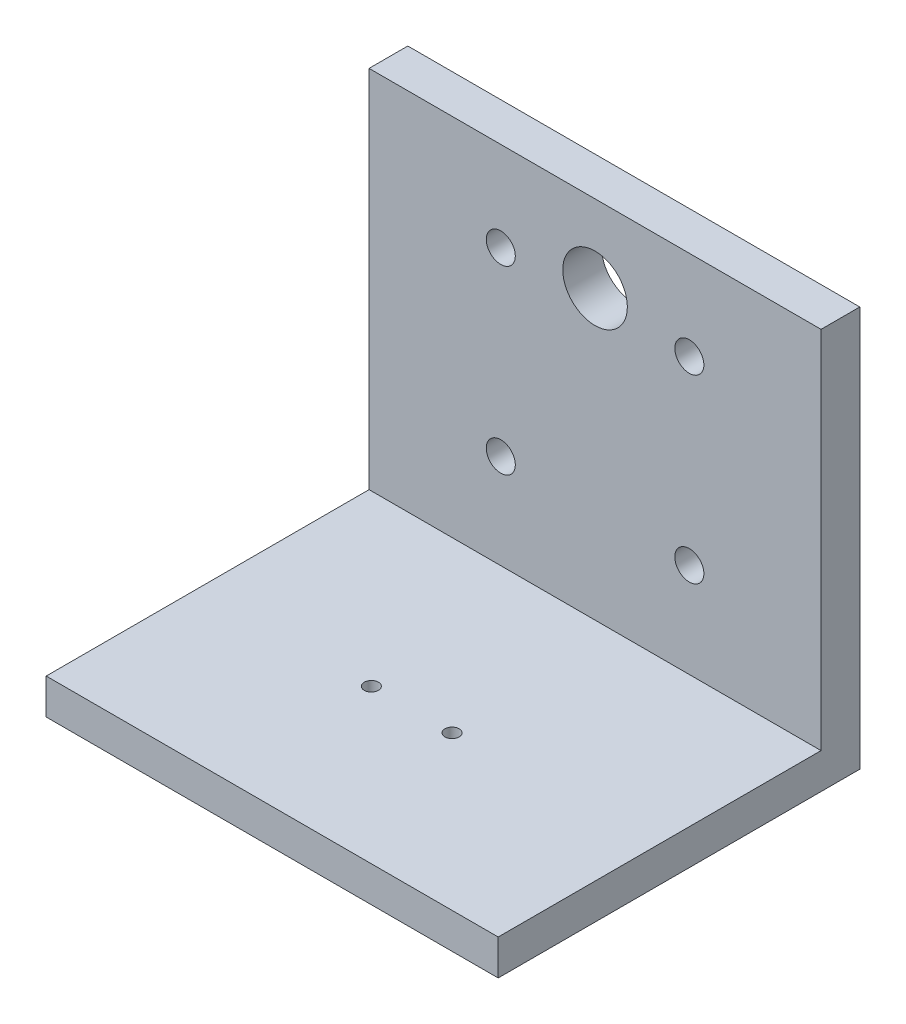
SolidWorks part; units mm, degrees
ref_plane "Plan de face" through (0, 0, 0) normal (0, 0, 1) x (1, 0, 0)
ref_plane "Plan de dessus" through (0, 0, 0) normal (0, 1, 0) x (1, 0, 0)
ref_plane "Plan de droite" through (0, 0, 0) normal (1, 0, 0) x (0, 0, -1)
sketch "Esquisse1" plane through (0, 0, 0) normal (0, 0, 1) x (1, 0, 0)
  line L1 (-33.4364, 20.6028) -> (36.5636, 20.6028)
  line L2 (-33.4364, 20.6028) -> (-33.4364, -41.3972)
  line L3 (-33.4364, -41.3972) -> (36.5636, -41.3972)
  line L4 (36.5636, 20.6028) -> (36.5636, -41.3972)
  circle A0 centre (-13.0364, 6.7528) radius 2.25
  circle A1 centre (16.1636, 6.7528) radius 2.25
  circle A2 centre (-13.0364, -21.2472) radius 2.25
  circle A3 centre (16.1636, -21.2472) radius 2.25
  dimension "D8" = 4.5
  dimension "D9" = 4.5
  dimension "D10" = 4.5
  dimension "D11" = 4.5
  dimension "D1" = 70
  dimension "D2" = 62
  dimension "D3" = 20.4
  dimension "D4" = 13.85
  dimension "D5" = 20.4
  dimension "D6" = 28
  dimension "D7" = 28
extrude "Boss.-Extru.3" add sketch "Esquisse1" along normal blind 6
sketch "Esquisse3" plane through (0, 0, 6) normal (0, 0, 1) x (1, 0, 0)
  line L0 (36.5636, -41.3972) -> (36.5636, 20.6028) construction
  line L1 (-33.4364, -41.3972) -> (36.5636, -41.3972)
  line L2 (-33.4364, -41.3972) -> (-33.4364, -35.8972)
  line L3 (-33.4364, -35.8972) -> (36.5636, -35.8972)
  line L4 (36.5636, -41.3972) -> (36.5636, -35.8972)
  dimension "D1" = 5.5
extrude "Boss.-Extru.4" add sketch "Esquisse3" along normal blind 50
sketch "Esquisse4" plane through (0, -35.8972, 0) normal (0, 1, 0) x (1, 0, 0)
  line L0 (-33.4364, -56) -> (-33.4364, -6) construction
  circle A0 centre (-6.8864, -32.1944) radius 1.1
  circle A1 centre (5.6136, -32.1944) radius 1.1
  dimension "D1" = 2.2
  dimension "D2" = 2.2
  dimension "D3" = 12.5
  dimension "D4" = 26.55
extrude "Enlèv. mat.-Extru.1" cut sketch "Esquisse4" against normal through all
sketch "Esquisse5" plane through (0, 0, 0) normal (0, 0, -1) x (-1, 0, 0)
  line L0 (-36.5636, 20.6028) -> (33.4364, 20.6028) construction
  line L1 (-36.5636, -41.3972) -> (-36.5636, 20.6028) construction
  circle A0 centre (-1.5636, 8.6028) radius 5
  dimension "D1" = 10
  dimension "D2" = 12
  dimension "D3" = 35
extrude "Enlèv. mat.-Extru.2" cut sketch "Esquisse5" against normal blind 50
